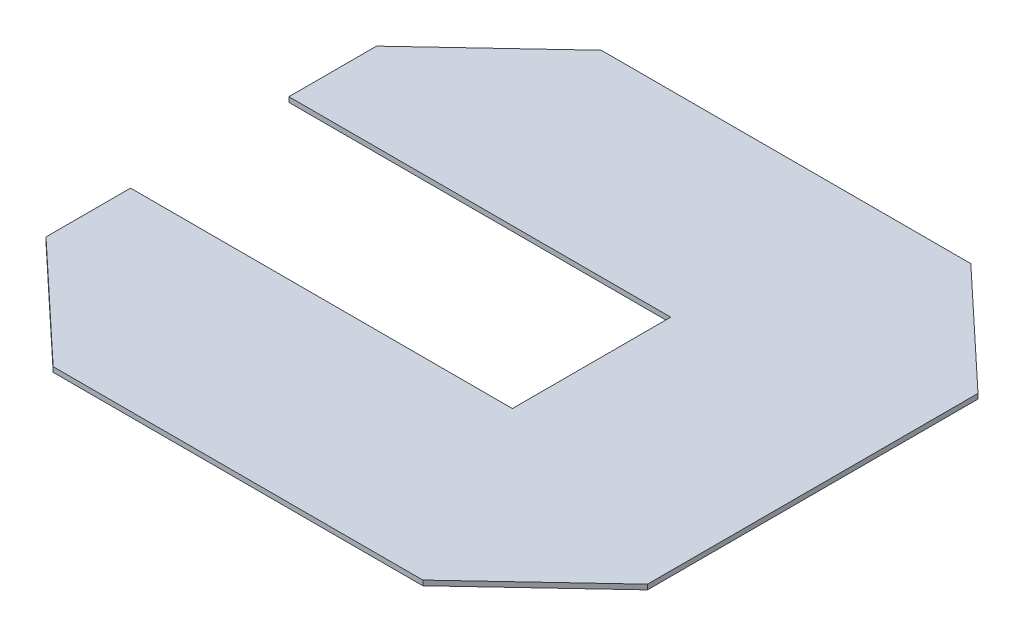
SolidWorks part; units mm, degrees
ref_plane "Спереди" through (0, 0, 0) normal (0, 0, 1) x (1, 0, 0)
ref_plane "Сверху" through (0, 0, 0) normal (0, 1, 0) x (1, 0, 0)
ref_plane "Справа" through (0, 0, 0) normal (1, 0, 0) x (0, 0, -1)
sketch "Эскиз1" plane through (0, 0, 0) normal (0, 1, 0) x (1, 0, 0)
  line L0 (-94.4415, -137.7523) -> (-153.0725, -82.7523)
  line L1 (-94.4415, 139.3656) -> (92.4315, 139.3656)
  line L2 (-126.7104, 0.8067) -> (-201.1681, 0.8067) construction
  line L3 (-153.0725, 84.3656) -> (-153.0725, 40.0618)
  line L4 (-1.005, 120.7582) -> (-1.005, 306.7026) construction
  line L5 (-153.0725, 84.3656) -> (-94.4415, 139.3656)
  line L6 (92.4315, -137.7523) -> (151.0625, -82.7523)
  line L7 (151.0625, 84.3656) -> (151.0625, -82.7523)
  line L8 (-94.4415, -137.7523) -> (92.4315, -137.7523)
  line L9 (151.0625, 84.3656) -> (92.4315, 139.3656)
  line L10 (-153.0725, -40) -> (-153.0725, -82.7523)
  line L11 (-153.0725, 40.0618) -> (40, 40.0618)
  line L13 (-153.0725, -40) -> (40, -40)
  line L14 (40, 40.0618) -> (40, -40)
extrude "Вытянуть1" add sketch "Эскиз1" along normal blind 2.5
